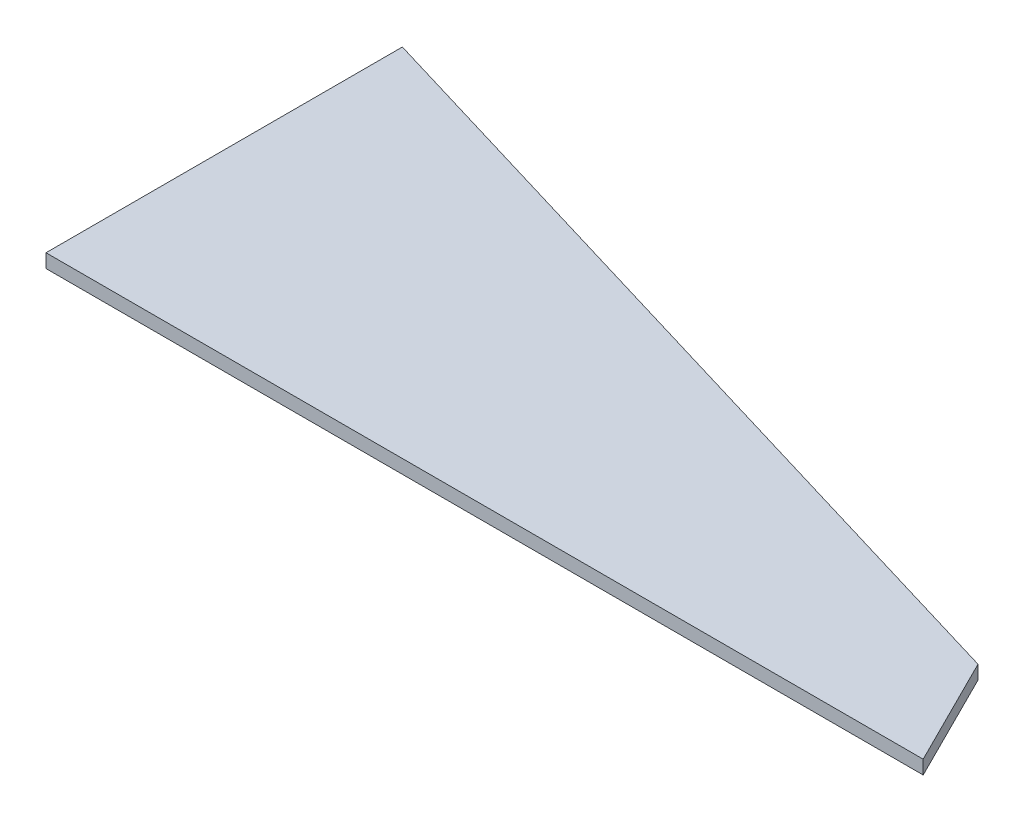
SolidWorks part; units mm, degrees
ref_plane "Front Plane" through (0, 0, 0) normal (0, 0, 1) x (1, 0, 0)
ref_plane "Top Plane" through (0, 0, 0) normal (0, 1, 0) x (1, 0, 0)
ref_plane "Right Plane" through (0, 0, 0) normal (1, 0, 0) x (0, 0, -1)
sketch "Sketch1" plane through (0, 0, 0) normal (0, 1, 0) x (1, 0, 0)
  line L0 (-22.4, -13) -> (9.6, -13)
  line L1 (-22.4, -13) -> (-22.4, 0)
  line L2 (-22.4, 0) -> (7.6, -9)
  line L3 (7.6, -9) -> (9.6, -13)
  dimension "D1" = 32
  dimension "D2" = 13
  dimension "D3" = 30
  dimension "D4" = 4
extrude "Boss-Extrude1" add sketch "Sketch1" along normal blind 0.5
